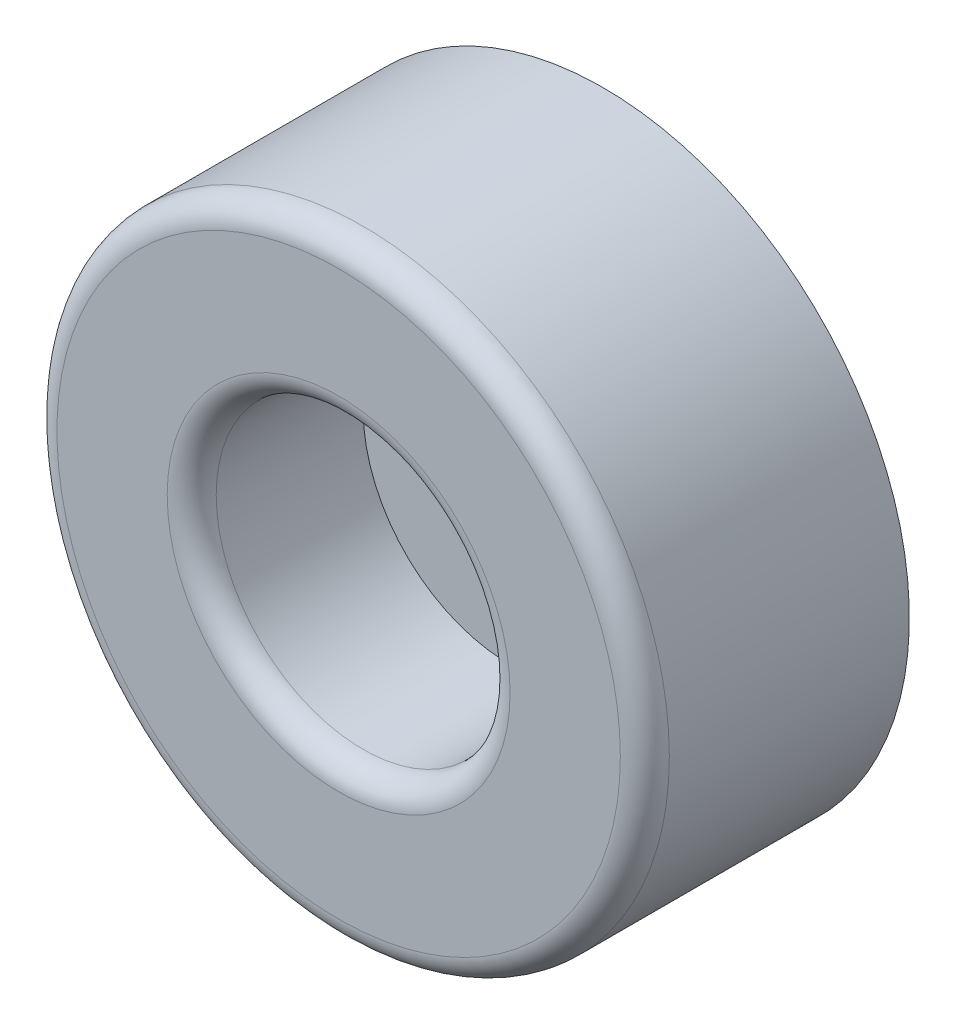
SolidWorks part; units mm, degrees
ref_plane "Ebene vorne" through (0, 0, 0) normal (1, 0, 0) x (0, 1, 0)
ref_plane "Ebene oben" through (0, 0, 0) normal (0, 0, 1) x (0, 1, 0)
ref_plane "Ebene rechts" through (0, 0, 0) normal (0, 1, 0) x (-1, 0, 0)
sketch "Skizze1" plane through (0, 0, 0) normal (0, 0, 1) x (0, 1, 0)
  circle A0 centre (0, 0) radius 12.5
  dimension "D1" = 25
extrude "Aufsatz-Linear austragen1" add sketch "Skizze1" along normal blind 10.8
sketch "Skizze2" plane through (0, 0, 10.8) normal (0, 0, 1) x (1, 0, 0)
  circle A0 centre (0, 0) radius 6
  dimension "D1" = 12
extrude "Schnitt-Linear austragen1" cut sketch "Skizze2" against normal blind 7
sketch "Skizze3" plane through (0, 0, 3.8) normal (0, 0, 1) x (1, 0, 0)
  circle A0 centre (0, 0) radius 2.5
  dimension "D1" = 5
extrude "Schnitt-Linear austragen2" cut sketch "Skizze3" against normal through all both and the other way through all
fillet "Verrundung1" radius 1 2 edges at (12.5, 0, 10.8) (6, 0, 10.8)
